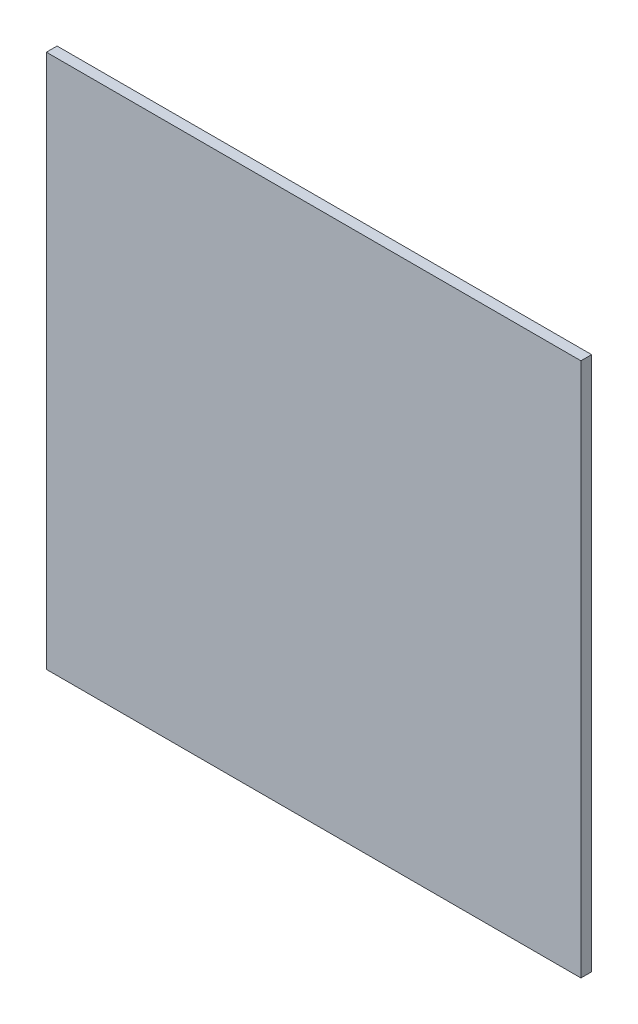
SolidWorks part; units mm, degrees
material "6061-T6 (SS)"
ref_plane "정면" through (0, 0, 0) normal (0, 0, 1) x (1, 0, 0)
ref_plane "윗면" through (0, 0, 0) normal (0, 1, 0) x (1, 0, 0)
ref_plane "우측면" through (0, 0, 0) normal (1, 0, 0) x (0, 0, -1)
sketch "스케치1" plane through (0, 0, 0) normal (0, 0, 1) x (1, 0, 0)
  line L1 (-125, 125) -> (125, 125)
  line L2 (-125, 125) -> (-125, -125)
  line L3 (-125, -125) -> (125, -125)
  line L4 (125, 125) -> (125, -125)
  line L5 (-125, 125) -> (125, -125) construction
  line L6 (-125, -125) -> (125, 125) construction
  point P0 (0, 0)
  dimension "D1" = 250
  dimension "D2" = 250
extrude "보스-돌출1" add sketch "스케치1" along normal blind 5
